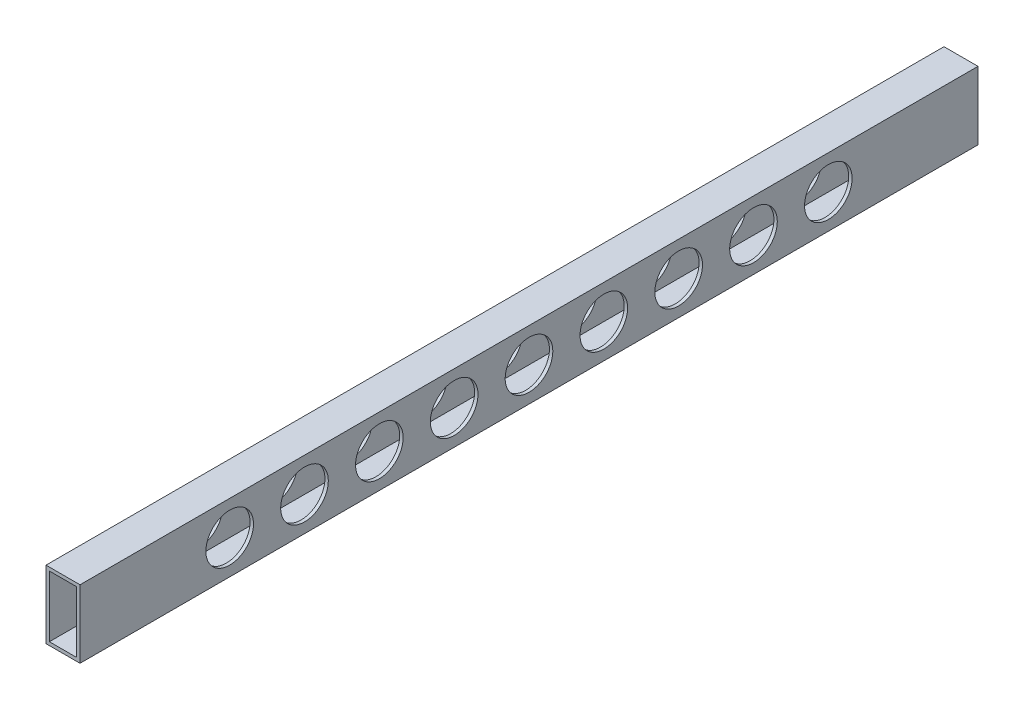
SolidWorks part; units mm, degrees
ref_plane "Front Plane" through (0, 0, 0) normal (0, 0, 1) x (1, 0, 0)
ref_plane "Top Plane" through (0, 0, 0) normal (0, 1, 0) x (1, 0, 0)
ref_plane "Right Plane" through (0, 0, 0) normal (1, 0, 0) x (0, 0, -1)
sketch "Sketch1" plane through (0, 0, 0) normal (0, 0, 1) x (1, 0, 0)
  line L1 (0, 0) -> (31.75, 0)
  line L2 (0, 0) -> (0, 63.5)
  line L3 (0, 63.5) -> (31.75, 63.5)
  line L4 (31.75, 0) -> (31.75, 63.5)
  line L5 (3.175, 3.175) -> (28.575, 3.175)
  line L6 (3.175, 3.175) -> (3.175, 60.325)
  line L7 (3.175, 60.325) -> (28.575, 60.325)
  line L8 (28.575, 3.175) -> (28.575, 60.325)
  dimension "D1" = 63.5
  dimension "D2" = 31.75
  dimension "D3" = 3.175
  dimension "D4" = 3.175
  dimension "D5" = 3.175
  dimension "D6" = 3.175
extrude "Boss-Extrude1" add sketch "Sketch1" along normal blind 838.2
sketch "Sketch2" plane through (31.75, 0, 0) normal (1, 0, 0) x (0, 0, -1)
  line L0 (-838.2, 0) -> (-838.2, 63.5) construction
  line L1 (-838.2, 0) -> (0, 0) construction
  circle A0 centre (-698.5, 31.75) radius 22.225
  circle A1 centre (-628.65, 31.75) radius 22.225
  circle A2 centre (-558.8, 31.75) radius 22.225
  circle A3 centre (-488.95, 31.75) radius 22.225
  circle A4 centre (-419.1, 31.75) radius 22.225
  circle A5 centre (-349.25, 31.75) radius 22.225
  circle A6 centre (-279.4, 31.75) radius 22.225
  circle A7 centre (-209.55, 31.75) radius 22.225
  circle A8 centre (-139.7, 31.75) radius 22.225
  dimension "D2" = 44.45
  dimension "D1" = 139.7
  dimension "D3" = 31.75
  dimension "D4" = 9
extrude "Cut-Extrude1" cut sketch "Sketch2" along direction (1, 0, 0) on the side against the normal blind 31.75
